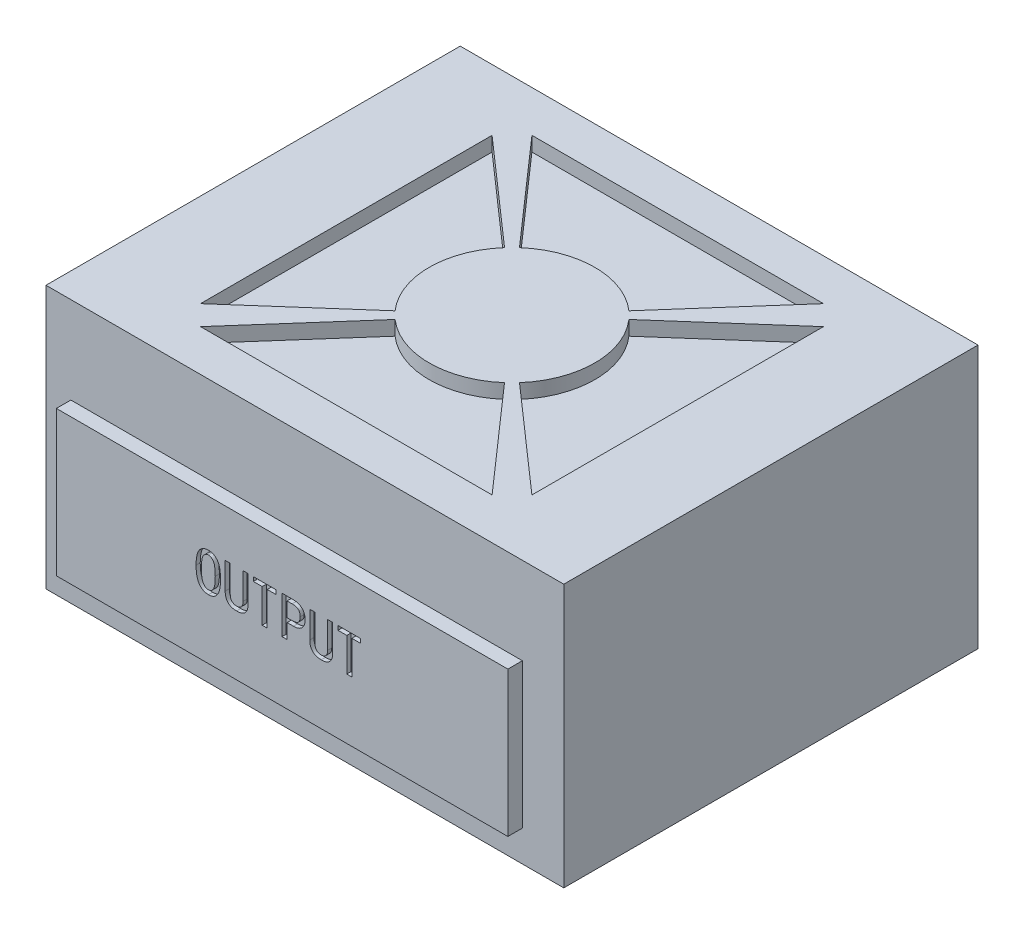
SolidWorks part; units mm, degrees
ref_plane "前视基准面" through (0, 0, 0) normal (0, 0, 1) x (1, 0, 0)
ref_plane "上视基准面" through (0, 0, 0) normal (0, 1, 0) x (1, 0, 0)
ref_plane "右视基准面" through (0, 0, 0) normal (1, 0, 0) x (0, 0, -1)
sketch "草图1" plane through (0, 0, 0) normal (0, 1, 0) x (1, 0, 0)
  line L1 (-62.5, -50) -> (62.5, -50)
  line L2 (-62.5, -50) -> (-62.5, 50)
  line L3 (-62.5, 50) -> (62.5, 50)
  line L4 (62.5, -50) -> (62.5, 50)
  line L5 (-62.5, -50) -> (62.5, 50) construction
  line L6 (-62.5, 50) -> (62.5, -50) construction
  point P0 (0, 0)
  dimension "D1" = 100
  dimension "D2" = 125
extrude "凸台-拉伸1" add sketch "草图1" along normal blind 63.5
sketch "草图2" plane through (0, 0, 50) normal (0, 0, 1) x (1, 0, 0)
  line L0 (62.5, 63.5) -> (62.5, 0) construction
  line L1 (-56.5, 42.5) -> (52.5, 42.5)
  line L2 (-56.5, 42.5) -> (-56.5, 7.5)
  line L3 (-56.5, 7.5) -> (52.5, 7.5)
  line L4 (52.5, 42.5) -> (52.5, 7.5)
  line L5 (-62.5, 63.5) -> (-62.5, 0) construction
  line L6 (-62.5, 0) -> (62.5, 0) construction
  line L7 (-62.5, 63.5) -> (62.5, 63.5) construction
  dimension "D1" = 10
  dimension "D2" = 6
  dimension "D3" = 7.5
  dimension "D4" = 21
extrude "凸台-拉伸2" add sketch "草图2" along normal blind 3.5
sketch "草图3" plane through (0, 63.5, 0) normal (0, 1, 0) x (1, 0, 0)
  line L0 (-35.1906, 40) -> (35.1906, 40)
  line L1 (35.1906, 40) -> (13.2106, 15.016)
  line L2 (-13.2106, 15.016) -> (-35.1906, 40)
  line L3 (62.5, 50) -> (-62.5, 50) construction
  line L4 (-62.5, 50) -> (0, 0) construction
  line L5 (0, 0) -> (62.5, 50) construction
  line L6 (15.016, 13.2106) -> (40, 35.1906)
  line L7 (40, 35.1906) -> (40, -35.1906)
  line L8 (40, -35.1906) -> (15.016, -13.2106)
  line L9 (13.2106, -15.016) -> (35.1906, -40)
  line L10 (35.1906, -40) -> (-35.1906, -40)
  line L11 (-35.1906, -40) -> (-13.2106, -15.016)
  line L12 (-15.016, -13.2106) -> (-40, -35.1906)
  line L13 (-40, -35.1906) -> (-40, 35.1906)
  line L14 (-40, 35.1906) -> (-15.016, 13.2106)
  arc A1 (13.2106, 15.016) -> (-13.2106, 15.016) centre (0, 0) ccw
  arc A2 (15.016, -13.2106) -> (15.016, 13.2106) centre (0, 0) ccw
  arc A3 (-13.2106, -15.016) -> (13.2106, -15.016) centre (0, 0) ccw
  arc A4 (-15.016, 13.2106) -> (-15.016, -13.2106) centre (0, 0) ccw
  point P27 (0, 0)
  dimension "D1" = 20
  dimension "D2" = 10
  dimension "D3" = 10
  dimension "D4" = 10
  dimension "D5" = 4
extrude "切除-拉伸1" cut sketch "草图3" against normal blind 3.5 contours L2 L0 L1 A1 | L12 L13 L14 A4 | L9 L10 L11 A3 | L6 L7 L8 A2
sketch "草图4" plane through (0, 0, -50) normal (0, 0, -1) x (-1, 0, 0)
  line L0 (47.5, 4.5) -> (-12.5, 4.5) construction
  line L1 (47.5, 2) -> (-12.5, 2)
  line L2 (47.5, 7) -> (-12.5, 7)
  line L3 (-62.5, 0) -> (62.5, 0) construction
  line L4 (62.5, 63.5) -> (62.5, 0) construction
  line L5 (47.5, 14.7857) -> (-12.5, 14.7857)
  line L6 (47.5, 9.7857) -> (-12.5, 9.7857)
  line L7 (47.5, 12.2857) -> (-12.5, 12.2857) construction
  line L8 (47.5, 22.5714) -> (-12.5, 22.5714)
  line L9 (47.5, 17.5714) -> (-12.5, 17.5714)
  line L10 (47.5, 20.0714) -> (-12.5, 20.0714) construction
  line L11 (47.5, 30.3571) -> (-12.5, 30.3571)
  line L12 (47.5, 25.3571) -> (-12.5, 25.3571)
  line L13 (47.5, 27.8571) -> (-12.5, 27.8571) construction
  line L14 (47.5, 38.1429) -> (-12.5, 38.1429)
  line L15 (47.5, 33.1429) -> (-12.5, 33.1429)
  line L16 (47.5, 35.6429) -> (-12.5, 35.6429) construction
  line L17 (47.5, 45.9286) -> (-12.5, 45.9286)
  line L18 (47.5, 40.9286) -> (-12.5, 40.9286)
  line L19 (47.5, 43.4286) -> (-12.5, 43.4286) construction
  line L20 (47.5, 53.7143) -> (-12.5, 53.7143)
  line L21 (47.5, 48.7143) -> (-12.5, 48.7143)
  line L22 (47.5, 51.2143) -> (-12.5, 51.2143) construction
  line L23 (47.5, 61.5) -> (-12.5, 61.5)
  line L24 (47.5, 56.5) -> (-12.5, 56.5)
  line L25 (47.5, 59) -> (-12.5, 59) construction
  line L26 (-62.5, 63.5) -> (62.5, 63.5) construction
  arc A0 (47.5, 2) -> (47.5, 7) centre (47.5, 4.5) ccw
  arc A1 (-12.5, 7) -> (-12.5, 2) centre (-12.5, 4.5) ccw
  arc A2 (47.5, 9.7857) -> (47.5, 14.7857) centre (47.5, 12.2857) ccw
  arc A3 (-12.5, 14.7857) -> (-12.5, 9.7857) centre (-12.5, 12.2857) ccw
  arc A4 (47.5, 17.5714) -> (47.5, 22.5714) centre (47.5, 20.0714) ccw
  arc A5 (-12.5, 22.5714) -> (-12.5, 17.5714) centre (-12.5, 20.0714) ccw
  arc A6 (47.5, 25.3571) -> (47.5, 30.3571) centre (47.5, 27.8571) ccw
  arc A7 (-12.5, 30.3571) -> (-12.5, 25.3571) centre (-12.5, 27.8571) ccw
  arc A8 (47.5, 33.1429) -> (47.5, 38.1429) centre (47.5, 35.6429) ccw
  arc A9 (-12.5, 38.1429) -> (-12.5, 33.1429) centre (-12.5, 35.6429) ccw
  arc A10 (47.5, 40.9286) -> (47.5, 45.9286) centre (47.5, 43.4286) ccw
  arc A11 (-12.5, 45.9286) -> (-12.5, 40.9286) centre (-12.5, 43.4286) ccw
  arc A12 (47.5, 48.7143) -> (47.5, 53.7143) centre (47.5, 51.2143) ccw
  arc A13 (-12.5, 53.7143) -> (-12.5, 48.7143) centre (-12.5, 51.2143) ccw
  arc A14 (47.5, 56.5) -> (47.5, 61.5) centre (47.5, 59) ccw
  arc A15 (-12.5, 61.5) -> (-12.5, 56.5) centre (-12.5, 59) ccw
  point P2 (17.5, 4.5)
  point P7 (22.5, 58.8349)
  point P14 (17.5, 12.2857)
  point P21 (17.5, 20.0714)
  point P28 (17.5, 27.8571)
  point P35 (17.5, 35.6429)
  point P42 (17.5, 43.4286)
  point P49 (17.5, 51.2143)
  point P56 (17.5, 59)
  dimension "D1" = 2
  dimension "D2" = 5
  dimension "D3" = 60
  dimension "D4" = 15
  dimension "D6" = 2
  dimension "D5" = 8
extrude "切除-拉伸2" cut sketch "草图4" against normal blind 1
sketch "草图5" plane through (0, 0, -50) normal (0, 0, -1) x (-1, 0, 0)
  line L0 (-62.5, 63.5) -> (-62.5, 0) construction
  line L1 (-21, 21) -> (-52, 21)
  line L2 (-21, 21) -> (-21, 45)
  line L3 (-21, 45) -> (-52, 45)
  line L4 (-52, 21) -> (-52, 45)
  line L5 (-62.5, 63.5) -> (62.5, 63.5) construction
  dimension "D1" = 31
  dimension "D2" = 24
  dimension "D3" = 10.5
  dimension "D4" = 18.5
extrude "凸台-拉伸3" add sketch "草图5" along normal blind 3.2
sketch "草图6" plane through (0, 0, -53.2) normal (0, 0, -1) x (-1, 0, 0)
  line L0 (-23.5, 23.5) -> (-23.5, 36.5)
  line L1 (-23.5, 36.5) -> (-29.5, 42.5)
  line L2 (-29.5, 42.5) -> (-43.5, 42.5)
  line L3 (-43.5, 42.5) -> (-49.5, 36.5)
  line L4 (-49.5, 36.5) -> (-49.5, 23.5)
  line L5 (-49.5, 23.5) -> (-23.5, 23.5)
  line L6 (-52, 21) -> (-21, 21) construction
  line L7 (-21, 21) -> (-21, 45) construction
  line L8 (-21, 45) -> (-52, 45) construction
  line L10 (-27.5, 26.5) -> (-29, 26.5)
  line L11 (-27.5, 26.5) -> (-27.5, 29.5)
  line L12 (-27.5, 29.5) -> (-29, 29.5)
  line L13 (-29, 26.5) -> (-29, 29.5)
  line L14 (-35.75, 36.5) -> (-37.25, 36.5)
  line L15 (-35.75, 36.5) -> (-35.75, 39.5)
  line L16 (-35.75, 39.5) -> (-37.25, 39.5)
  line L17 (-37.25, 36.5) -> (-37.25, 39.5)
  line L18 (-44, 26.5) -> (-45.5, 26.5)
  line L19 (-44, 26.5) -> (-44, 29.5)
  line L20 (-44, 29.5) -> (-45.5, 29.5)
  line L21 (-45.5, 26.5) -> (-45.5, 29.5)
  point P7 (-36.5, 42.5)
  point P8 (-36.5, 23.5)
  point P12 (-36.5, 21)
  point P27 (-36.5, 39.5)
  point P28 (-31.3622, 26.8715)
  dimension "D1" = 2.5
  dimension "D2" = 2.5
  dimension "D3" = 2.5
  dimension "D4" = 14
  dimension "D5" = 3
  dimension "D6" = 4
  dimension "D7" = 4
  dimension "D8" = 1.5
  dimension "D9" = 3
  dimension "D10" = 3
extrude "切除-拉伸3" cut sketch "草图6" against normal blind 20
sketch "草图7" plane through (0, 0, -50) normal (0, 0, -1) x (-1, 0, 0)
  line L0 (-52, 21) -> (-21, 21) construction
  line L1 (-26, 21) -> (-47, 21)
  line L2 (-26, 21) -> (-26, 11)
  line L3 (-26, 11) -> (-47, 11)
  line L4 (-47, 21) -> (-47, 11)
  line L6 (-36.5, 21) -> (-36.5, 45) construction
  line L7 (-21, 45) -> (-52, 45) construction
  line L8 (-52, 21) -> (-21, 21) construction
  dimension "D1" = 21
  dimension "D2" = 10
extrude "凸台-拉伸4" add sketch "草图7" along normal blind 2.3
sketch "草图8" plane through (0, 0, -52.3) normal (0, 0, -1) x (-1, 0, 0)
  line L0 (-47, 11) -> (-26, 11) construction
  line L5 (-31.5, 15.5) -> (-41.5, 15.5) construction
  line L6 (-31.5, 13) -> (-41.5, 13)
  line L7 (-31.5, 18) -> (-41.5, 18)
  arc A0 (-31.5, 13) -> (-31.5, 18) centre (-31.5, 15.5) ccw
  arc A1 (-41.5, 18) -> (-41.5, 13) centre (-41.5, 15.5) ccw
  point P2 (-36.5, 15.5)
  point P7 (-36.5, 11)
  point P10 (-29, 15.5)
  point P11 (-44, 15.5)
  dimension "D1" = 5
  dimension "D2" = 15
  dimension "D3" = 2
extrude "凸台-拉伸5" add sketch "草图8" along normal blind 4.2
sketch "草图9" plane through (0, 0, -50) normal (0, 0, -1) x (-1, 0, 0)
  line L0 (62.5, 0) -> (-62.5, 63.5) construction
  line L1 (62.5, 63.5) -> (62.5, 0) construction
  line L2 (56.5, 57.5) -> (-56.5, 57.5) construction
  line L3 (56.5, 57.5) -> (56.5, 6) construction
  line L4 (56.5, 6) -> (-56.5, 6) construction
  line L5 (-56.5, 57.5) -> (-56.5, 6) construction
  line L6 (56.5, 57.5) -> (-56.5, 6) construction
  line L7 (56.5, 6) -> (-56.5, 57.5) construction
  line L8 (-62.5, 0) -> (62.5, 0) construction
  point P4 (0, 31.75)
  point P9 (56.5, 31.75)
  point P10 (-56.5, 31.75)
  dimension "D1" = 6
  dimension "D2" = 6
hole_wizard "M3 螺纹孔1" positions "草图10" profile "草图12" tap size "M3" standard "GB"
sketch "草图10" plane through (0, 0, -50) normal (0, 0, -1) x (-1, 0, 0)
  point P0 (56.5, 6)
  point P3 (56.5, 31.75)
  point P6 (56.5, 57.5)
  point P9 (-56.5, 6)
  point P12 (-56.5, 31.75)
  point P15 (-56.5, 57.5)
sketch "草图12" plane through (-56.5, 6, -50) normal (1, 0, 0) x (0, 1, 0)
  line L0 (0, 0) -> (0, 9.2511)
  line L1 (0, 9.2511) -> (1.25, 8.5)
  line L2 (1.25, 8.5) -> (1.25, 0)
  line L5 (1.25, 0) -> (0, 0)
  line L10 (0, 9.2511) -> (-1.25, 8.5) construction
  line L11 (0, -6.35) -> (0, 107.95) construction
  dimension "螺纹孔钻头直径" = 2.5
  dimension "螺纹孔钻头深度" = 8.5
  dimension "导头角度" = 118
cosmetic thread "孔螺蚊线1" parameters "D1"=6, "D2"=3
cosmetic thread "孔螺蚊线2" parameters "D1"=6, "D2"=3
cosmetic thread "孔螺蚊线3" parameters "D1"=6, "D2"=3
cosmetic thread "孔螺蚊线4" parameters "D1"=6, "D2"=3
cosmetic thread "孔螺蚊线5" parameters "D1"=6, "D2"=3
cosmetic thread "孔螺蚊线6" parameters "D1"=6, "D2"=3
sketch "草图13" plane through (0, 0, 53.5) normal (0, 0, 1) x (1, 0, 0)
  line L0 (-33.2435, 21.7504) -> (27.8133, 21.7504) construction
  text T0 "OUTPUT" font "黑体" height in points 30
extrude "切除-拉伸4" cut sketch "草图13" against normal blind 1
